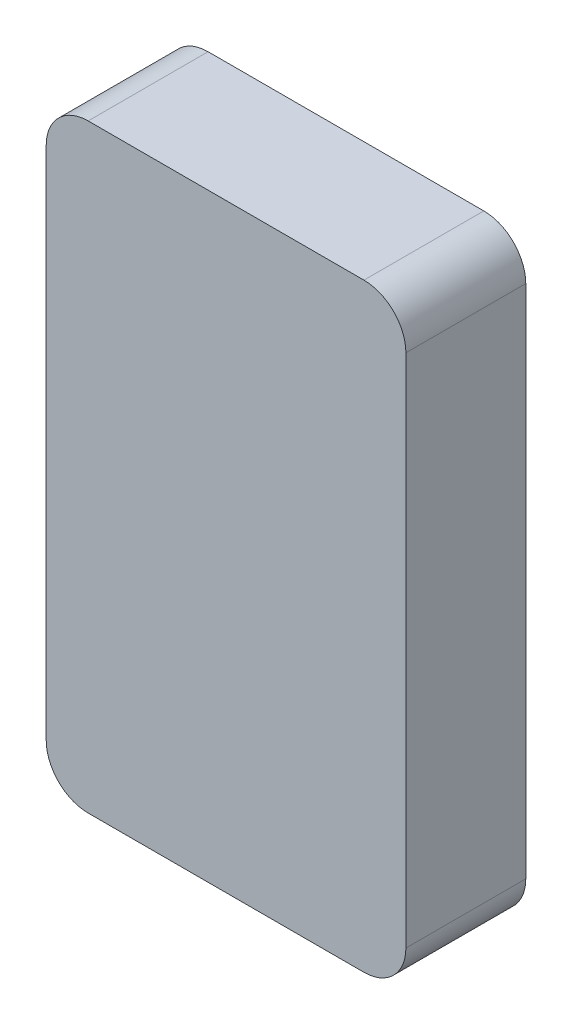
SolidWorks part; units mm, degrees
ref_plane "Front Plane" through (0, 0, 0) normal (0, 0, 1) x (1, 0, 0)
ref_plane "Top Plane" through (0, 0, 0) normal (0, 1, 0) x (1, 0, 0)
ref_plane "Right Plane" through (0, 0, 0) normal (1, 0, 0) x (0, 0, -1)
sketch "Sketch1" plane through (0, 0, 0) normal (0, 0, 1) x (1, 0, 0)
  line L1 (-150, -250) -> (150, -250)
  line L2 (-150, -250) -> (-150, 250)
  line L3 (-150, 250) -> (150, 250)
  line L4 (150, -250) -> (150, 250)
  line L5 (-150, -250) -> (150, 250) construction
  line L6 (-150, 250) -> (150, -250) construction
  point P0 (0, 0)
  dimension "D1" = 300
  dimension "D2" = 500
extrude "Boss-Extrude1" add sketch "Sketch1" against normal blind 100
fillet "Fillet1" radius 35 4 edges at (150, -250, -50) (-150, -250, -50) (150, 250, -50) (-150, 250, -50)
